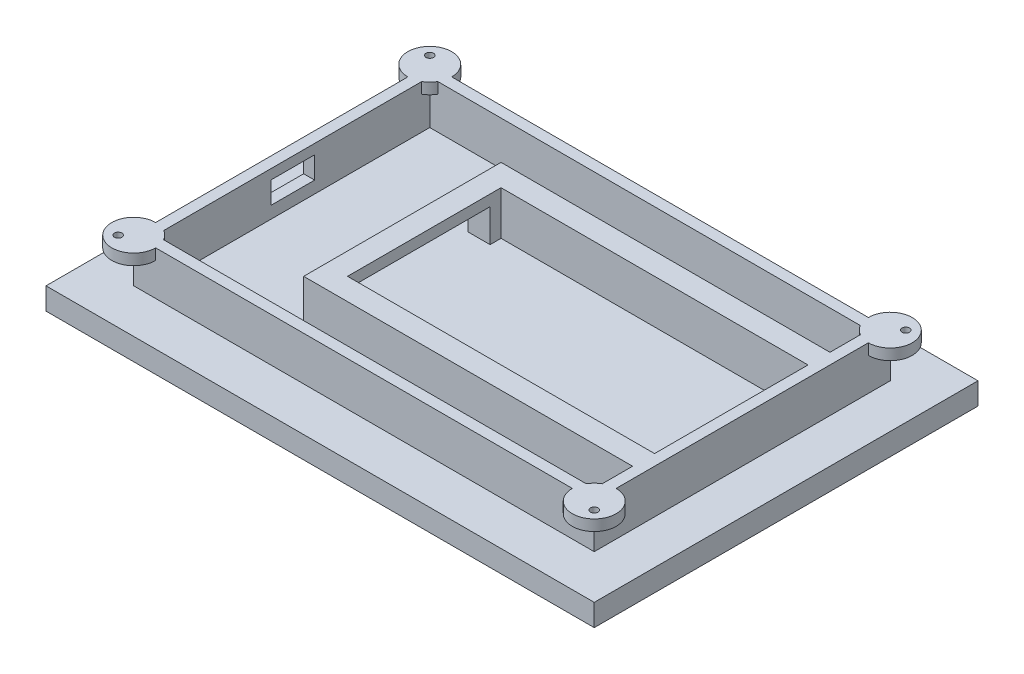
SolidWorks part; units mm, degrees
ref_plane "Front Plane" through (0, 0, 0) normal (0, 0, 1) x (1, 0, 0)
ref_plane "Top Plane" through (0, 0, 0) normal (0, 1, 0) x (1, 0, 0)
ref_plane "Right Plane" through (0, 0, 0) normal (1, 0, 0) x (0, 0, -1)
sketch "Sketch1" plane through (0, 0, 0) normal (0, 1, 0) x (1, 0, 0)
  line L0 (0, 0) -> (210, 0)
  line L1 (210, 0) -> (210, -135)
  line L2 (210, -135) -> (0, -135)
  line L3 (0, -135) -> (0, 0)
  line L4 (0, 0) -> (5, 0)
  line L5 (5, 0) -> (5, -130)
  line L6 (5, -130) -> (205, -130)
  line L7 (205, -130) -> (205, -5)
  line L8 (205, -5) -> (5, -5)
extrude "Boss-Extrude3" add sketch "Sketch1" along normal blind 40
sketch "Sketch3" plane through (0, 0, 0) normal (0, -1, 0) x (-1, 0, 0)
  line L0 (0, -135) -> (0, -145)
  line L1 (0, -145) -> (-220, -145)
  line L2 (-220, -145) -> (-220, 10)
  line L3 (-220, 10) -> (10, 10)
  line L4 (10, 10) -> (10, -145)
  line L5 (10, -145) -> (0, -145)
extrude "Boss-Extrude4" add sketch "Sketch3" along normal blind 10
sketch "Sketch4" plane through (0, 0, 0) normal (0, 1, 0) x (1, 0, 0)
  line L0 (205, -67.5) -> (205, -32.5)
  line L1 (205, -130) -> (205, -5) construction
  line L2 (205, -32.5) -> (65, -32.5)
  line L3 (65, -32.5) -> (65, -102.5)
  line L4 (65, -102.5) -> (205, -102.5)
  line L5 (205, -102.5) -> (205, -67.5)
  line L6 (205, -32.5) -> (205, -27.5)
  line L7 (205, -130) -> (205, -5) construction
  line L8 (205, -27.5) -> (60, -27.5)
  line L9 (60, -27.5) -> (60, -107.5)
  line L10 (60, -107.5) -> (205, -107.5)
  line L11 (205, -107.5) -> (205, -102.5)
extrude "Extrude-Thin1" add sketch "Sketch4" along normal blind 40 thin contours L2 L3 L4
sketch "Sketch5" plane through (55, 0, 0) normal (-1, 0, 0) x (0, 0, 1)
  line L0 (67.5, 0) -> (67.5, 15)
  line L1 (-10, 0) -> (145, 0) construction
  line L2 (67.5, 15) -> (97.5, 15)
  line L3 (97.5, 15) -> (97.5, 0)
  line L4 (135, 0) -> (0, 0) construction
  line L5 (97.5, 0) -> (37.5, 0)
  line L6 (37.5, 0) -> (37.5, 15)
  line L7 (37.5, 15) -> (67.5, 15)
extrude "Cut-Extrude2" cut sketch "Sketch5" against normal blind 40 contours L3 L2 L0 L1 | L7 L6 L1 L0
sketch "Sketch6" plane through (0, 40, 0) normal (0, 1, 0) x (1, 0, 0)
  line L0 (0, 0) -> (210, 0)
  line L1 (210, 0) -> (210, -135) construction
  line L2 (0, 0) -> (210, 0) construction
  line L3 (210, 0) -> (210, -135)
  line L4 (210, -135) -> (0, -135)
  line L5 (0, -135) -> (0, 0)
extrude "Cut-Extrude3" cut sketch "Sketch6" against normal blind 20
sketch "Sketch7" plane through (0, 20, 0) normal (0, 1, 0) x (1, 0, 0)
  circle A0 centre (0, 0) radius 10
  circle A1 centre (210, 0) radius 10
  circle A2 centre (210, -135) radius 10
  circle A3 centre (0, -135) radius 10
extrude "Boss-Extrude5" add sketch "Sketch7" against normal blind 5
sketch "Sketch8" plane through (0, 20, 0) normal (0, 1, 0) x (1, 0, 0)
  line L0 (0, 0) -> (-7.0711, 7.0711)
  line L1 (217.0711, 7.0711) -> (210, 0)
  line L2 (217.0711, -142.0711) -> (210, -135)
  line L3 (-7.0711, -142.0711) -> (0, -135)
  arc A0 (10, 0) -> (0, -10) centre (0, 0) ccw construction
  arc A1 (210, -10) -> (200, 0) centre (210, 0) ccw construction
  arc A2 (200, -135) -> (210, -125) centre (210, -135) ccw construction
  arc A3 (0, -125) -> (10, -135) centre (0, -135) ccw construction
  circle A4 centre (-3.5355, 3.5355) radius 1.7
  circle A5 centre (213.5355, 3.5355) radius 1.7
  circle A6 centre (213.5355, -138.5355) radius 1.7
  circle A7 centre (-3.5355, -138.5355) radius 1.7
extrude "Cut-Extrude5" cut sketch "Sketch8" against normal blind 5 contours A6 | A5 | A4 | A7
sketch "Sketch9" plane through (0, 0, 0) normal (-1, 0, 0) x (0, 0, 1)
  line L0 (67.5, 0) -> (67.5, 10.5)
  line L1 (135, 0) -> (0, 0) construction
  line L2 (67.5, 10.5) -> (77.5, 10.5)
  line L3 (77.5, 10.5) -> (77.5, 5.5)
  line L4 (77.5, 5.5) -> (57.5, 5.5)
  line L5 (57.5, 5.5) -> (57.5, 10.5)
  line L6 (57.5, 10.5) -> (67.5, 10.5)
  line L7 (57.5, 10.5) -> (57.5, 15.5)
  line L8 (57.5, 15.5) -> (77.5, 15.5)
  line L9 (77.5, 15.5) -> (77.5, 10.5)
  line L10 (77.5, 15.5) -> (77.5, 10.5)
extrude "Cut-Extrude6" cut sketch "Sketch9" against normal blind 10 contours L9 L8 L7 L6 L2 | L4 L3 L2 L0 | L6 L5 L4 L0
sketch "Sketch10" plane through (0, 0, 0) normal (0, 1, 0) x (1, 0, 0)
  line L0 (-10, 10) -> (-10, 20)
  line L1 (-10, 20) -> (230, 20)
  line L2 (230, 20) -> (230, -225)
  line L3 (230, -225) -> (-20, -225)
  line L4 (-20, -225) -> (-20, 20)
  line L5 (-20, 20) -> (-10, 20)
  line L6 (-10, 10) -> (220, 10)
  line L7 (220, 10) -> (220, -145)
  line L8 (220, -145) -> (-10, -145)
  line L9 (-10, -145) -> (-10, 10)
extrude "Boss-Extrude6" add sketch "Sketch10" against normal blind 10
sketch "Sketch12" plane through (-20, 0, 0) normal (-1, 0, 0) x (0, 0, 1)
  line L0 (135, 0) -> (155, 0)
  line L1 (225, 0) -> (-20, 0) construction
  line L2 (155, 0) -> (155, -10)
  line L3 (225, -10) -> (-20, -10) construction
  line L4 (155, -10) -> (225, -10)
  line L5 (225, -10) -> (225, 0)
  line L6 (225, 0) -> (155, 0)
  line M1 (225, 0) -> (-20, 0)
  line M3 (-20, -10) -> (225, -10)
  line M4 (225, -10) -> (225, 0)
extrude "Cut-Extrude7" cut sketch "Sketch12" against normal blind 250 contours L2 M1 M3 M4
